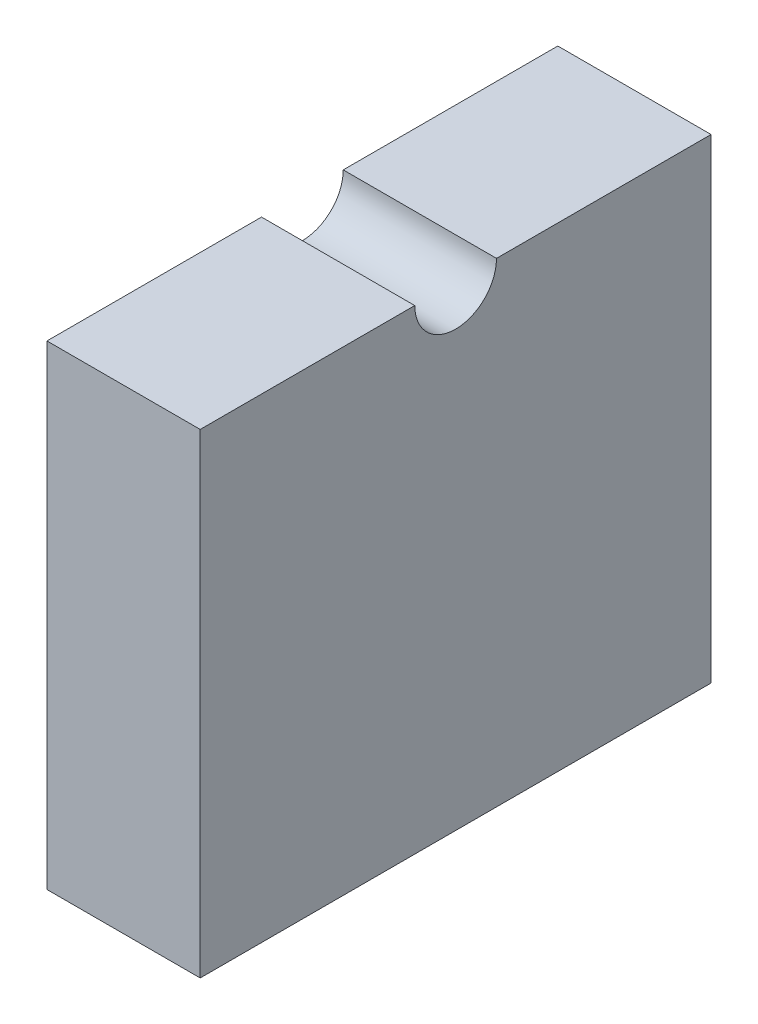
SolidWorks part; units mm, degrees
ref_plane "Alzado" through (0, 0, 0) normal (0, 0, 1) x (1, 0, 0)
ref_plane "Planta" through (0, 0, 0) normal (0, 1, 0) x (1, 0, 0)
ref_plane "Vista lateral" through (0, 0, 0) normal (1, 0, 0) x (0, 0, -1)
sketch "Croquis1" plane through (0, 0, 0) normal (1, 0, 0) x (0, 0, -1)
  line L0 (4, 23.25) -> (25, 23.25)
  line L1 (-25, 23.25) -> (-4, 23.25)
  line L2 (-25, 23.25) -> (-25, -23.25)
  line L3 (-25, -23.25) -> (25, -23.25)
  line L4 (25, 23.25) -> (25, -23.25)
  line L5 (-25, 23.25) -> (25, -23.25) construction
  line L6 (-25, -23.25) -> (25, 23.25) construction
  arc A0 (-4, 23.25) -> (4, 23.25) centre (0, 23.25) ccw
  point P0 (0, 0)
  point P7 (0, 0)
  dimension "D3" = 4
  dimension "D1" = 50
  dimension "D2" = 46.5
  dimension "D4" = 8
extrude "Saliente-Extruir1" add sketch "Croquis1" along normal blind 15
